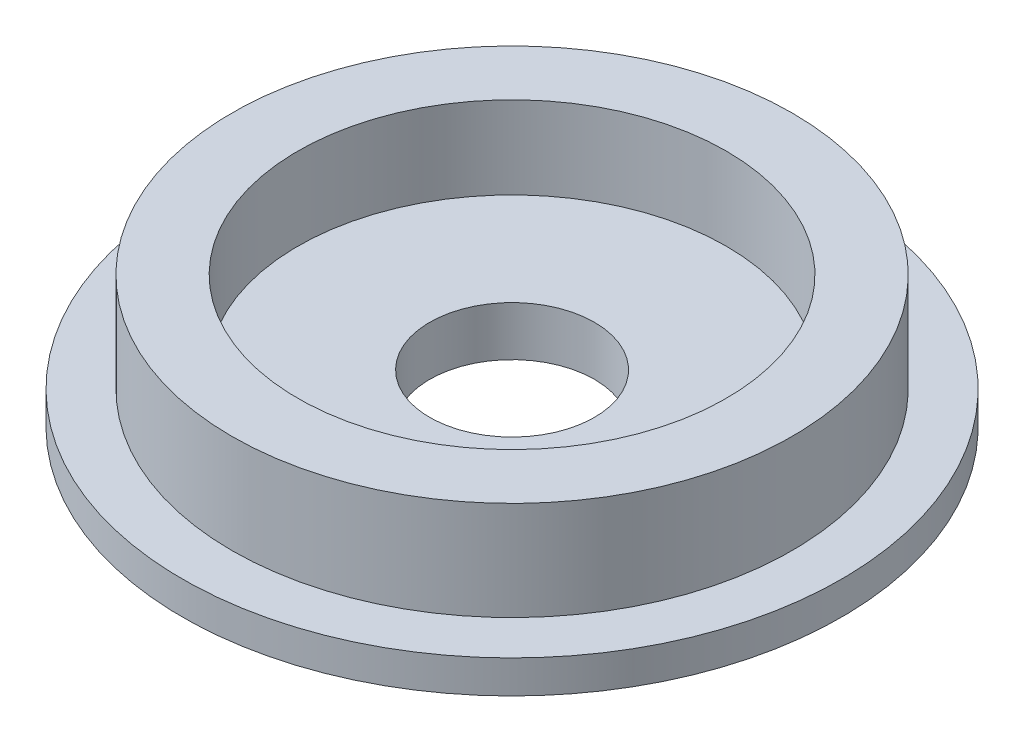
SolidWorks part; units mm, degrees
ref_plane "Front Plane" through (0, 0, 0) normal (0, 0, 1) x (1, 0, 0)
ref_plane "Top Plane" through (0, 0, 0) normal (0, 1, 0) x (1, 0, 0)
ref_plane "Right Plane" through (0, 0, 0) normal (1, 0, 0) x (0, 0, -1)
sketch "Sketch1" plane through (0, 0, 0) normal (1, 0, 0) x (0, 0, -1)
  line L0 (0, 0) -> (-2.5, 0)
  line L1 (-2.5, 0) -> (-2.5, 1.5)
  line L2 (-2.5, 1.5) -> (-6.5, 1.5)
  line L3 (-6.5, 1.5) -> (-6.5, 4)
  line L4 (-6.5, 4) -> (-8.5, 4)
  line L5 (-8.5, 4) -> (-8.5, 1)
  line L6 (-7.405, 0) -> (-2.5, 0)
  line L7 (-7.405, 0) -> (-10, 0)
  line L8 (-10, 0) -> (-10, 1)
  line L9 (-10, 1) -> (-8.5, 1)
  line L10 (0, 0) -> (0, 2.175) construction
  dimension "D1" = 13
  dimension "D2" = 5
  dimension "D3" = 3
  dimension "D4" = 2.5
  dimension "D5" = 10
  dimension "D6" = 2
  dimension "D7" = 1
revolve "Revolve1" add sketch "Sketch1" angle 360 about L10
